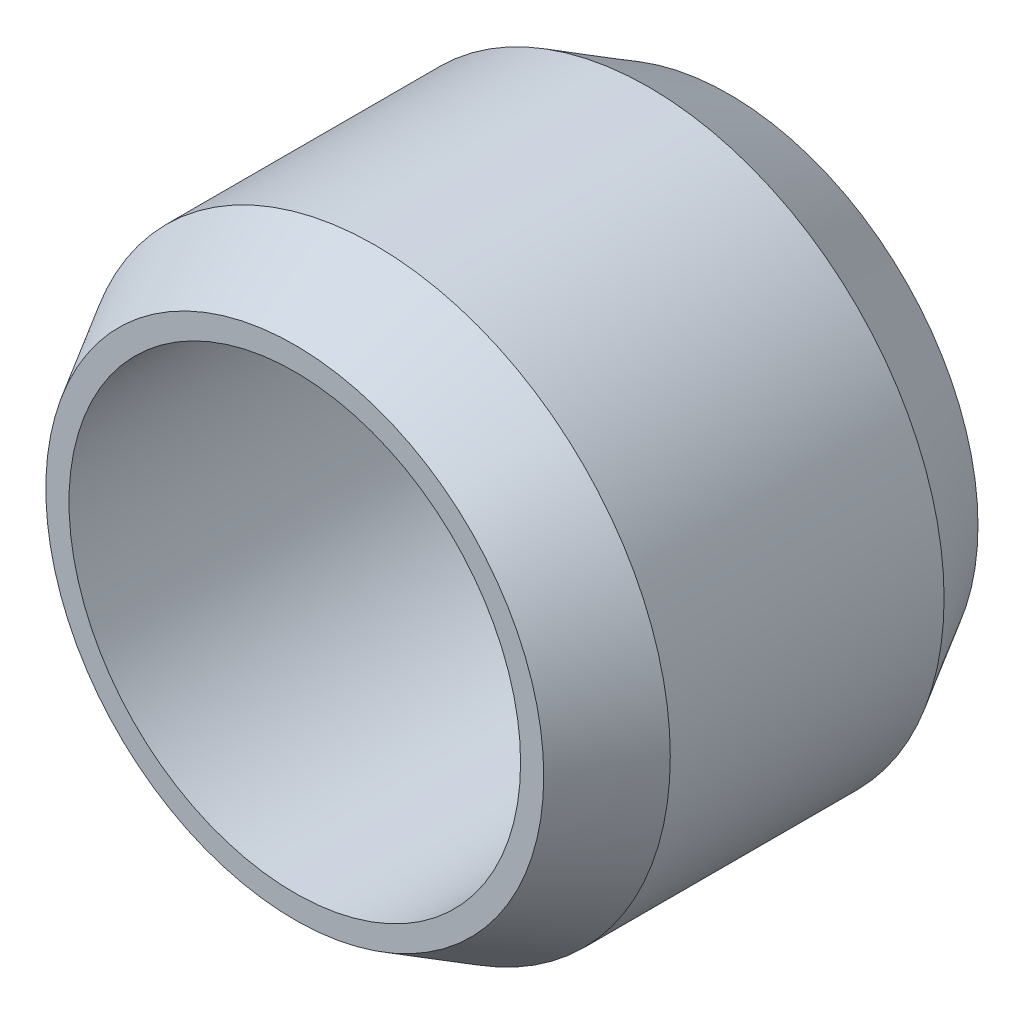
SolidWorks part; units mm, degrees
ref_plane "Front Plane" through (0, 0, 0) normal (0, 0, 1) x (1, 0, 0)
ref_plane "Top Plane" through (0, 0, 0) normal (0, 1, 0) x (1, 0, 0)
ref_plane "Right Plane" through (0, 0, 0) normal (1, 0, 0) x (0, 0, -1)
sketch "Sketch1" plane through (0, 0, 0) normal (1, 0, 0) x (0, 0, -1)
  line L0 (-3.175, 0) -> (3.175, 0) construction
  line L1 (-3.175, 3.302) -> (3.175, 3.302)
  line L2 (3.175, 3.302) -> (3.175, 3.6407)
  line L3 (3.175, 3.6407) -> (2.0018, 4.318)
  line L4 (2.0018, 4.318) -> (-2.0018, 4.318)
  line L5 (-3.175, 3.6407) -> (-2.0018, 4.318)
  line L6 (-3.175, 3.302) -> (-3.175, 3.6407)
  line L7 (-2.0018, 4.318) -> (-3.175, 4.318) construction
  line L8 (-3.175, 4.318) -> (-3.175, 3.9793) construction
  line L9 (-3.175, 3.9793) -> (-3.175, 3.6407) construction
  dimension "D1" = 30
  dimension "For Tube OD" = 6.604
  dimension "Major Diameter" = 8.636
  dimension "Length" = 6.35
sketch "Sketch2" plane through (0, 0, 0) normal (1, 0, 0) x (0, 0, -1)
  line L0 (-3.175, 3.302) -> (-3.175, 3.6407) construction
  line L1 (-3.175, 3.6407) -> (-2.0018, 4.318) construction
  line L2 (2.0018, 4.318) -> (-2.0018, 4.318) construction
  line L3 (3.175, 3.6407) -> (2.0018, 4.318) construction
  line L4 (3.175, 3.302) -> (3.175, 3.6407) construction
  line L5 (-3.175, 3.302) -> (3.175, 3.302) construction
  line L6 (-3.175, 3.302) -> (-3.175, 3.6407)
  line L7 (-3.175, 3.6407) -> (-2.0018, 4.318)
  line L8 (2.0018, 4.318) -> (-2.0018, 4.318)
  line L9 (3.175, 3.6407) -> (2.0018, 4.318)
  line L10 (3.175, 3.302) -> (3.175, 3.6407)
  line L11 (-3.175, 3.302) -> (3.175, 3.302)
revolve "Revolve1" add sketch "Sketch2" angle 360 about L0
